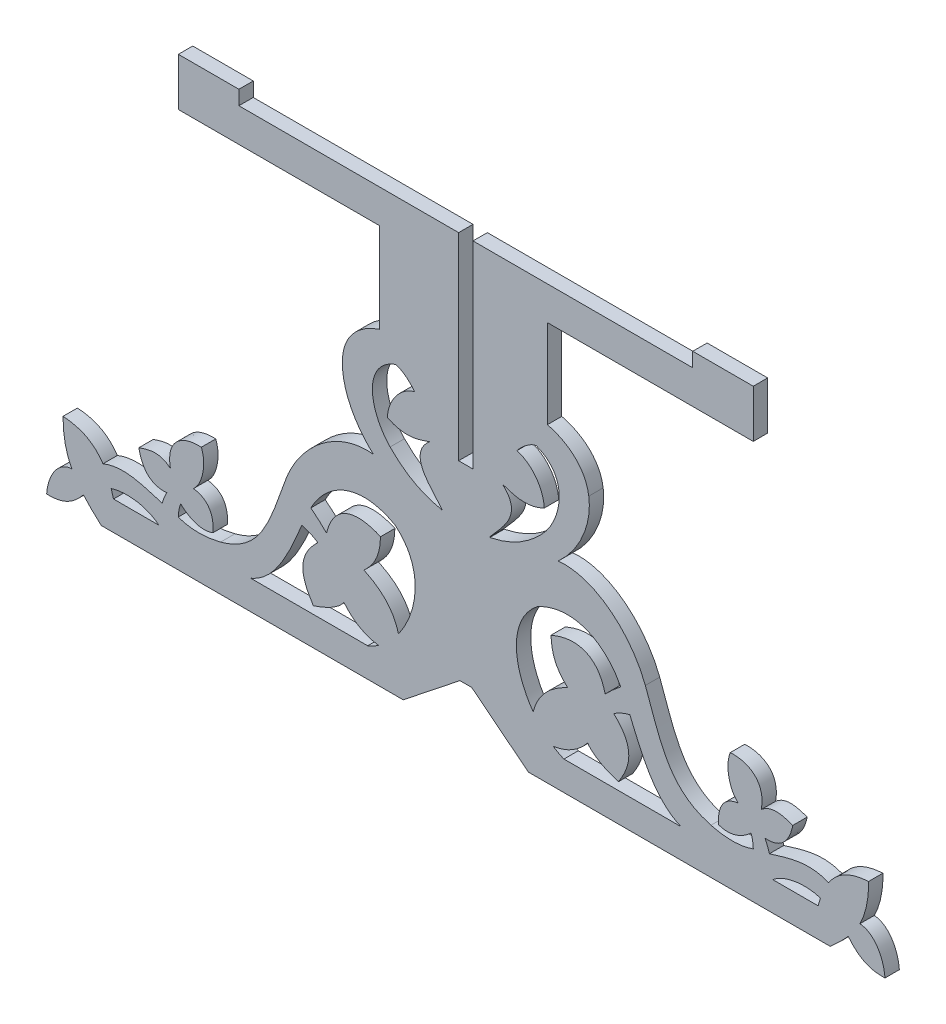
SolidWorks part; units mm, degrees
ref_plane "Plano frontal" through (0, 0, 0) normal (0, 0, 1) x (1, 0, 0)
ref_plane "Plano superior" through (0, 0, 0) normal (0, 1, 0) x (1, 0, 0)
ref_plane "Plano direito" through (0, 0, 0) normal (1, 0, 0) x (0, 0, -1)
sketch "Model" plane through (0, 0, 0) normal (0, 0, 1) x (1, 0, 0)
  line L0 (-10.7231, -37.6762) -> (-10.7231, -25.1897)
  line L1 (-10.7231, -25.1897) -> (-38.7386, -25.1897)
  line L2 (-38.7386, -18.5338) -> (-30.3175, -18.5338)
  line L3 (-30.3175, -18.5338) -> (-30.3175, -20.523)
  line L4 (-30.3175, -20.523) -> (0.2614, -20.523)
  line L5 (0.2614, -20.523) -> (0.2614, -48.0172)
  line L6 (0.2614, -48.0172) -> (2.2614, -48.0172)
  line L7 (2.2614, -48.0172) -> (2.2614, -20.523)
  line L8 (2.2614, -20.523) -> (32.8404, -20.523)
  line L9 (32.8404, -20.523) -> (32.8404, -18.5338)
  line L10 (32.8404, -18.5338) -> (41.2614, -18.5338)
  line L11 (41.2614, -25.1897) -> (12.6103, -25.1897)
  line L12 (12.6103, -25.1897) -> (12.6103, -37.4982)
  line L13 (51.9814, -80.6856) -> (9.9729, -80.6856)
  line L14 (9.9729, -80.6856) -> (2.0788, -74.4249)
  line L15 (2.0788, -74.4249) -> (0.4441, -74.4249)
  line L16 (0.4441, -74.4249) -> (-7.45, -80.6856)
  line L17 (-7.45, -80.6856) -> (-49.4585, -80.6856)
  line L18 (4.593, -55.0228) -> (4.593, -55.1006)
  line L19 (11.0703, -40.8025) -> (10.995, -40.8025)
  line L20 (-2.0702, -55.1006) -> (-2.0702, -55.0229)
  line L21 (-8.4723, -40.8025) -> (-8.5475, -40.8025)
  line L22 (31.2032, -76.6403) -> (14.9136, -76.6403)
  line L23 (50.289, -76.6403) -> (43.9782, -76.6403)
  line L24 (-28.6803, -76.6403) -> (-12.3907, -76.6403)
  line L25 (-47.7662, -76.6403) -> (-41.4553, -76.6403)
  spline S0 degree 3 poles (-49.4585, -80.6856) (-50.3937, -79.8491) (-51.2347, -79.0574) (-51.9577, -78.2277) knots 0 0 0 0 0.016393 0.016393 0.016393 0.016393
  spline S1 degree 3 poles (-51.9577, -78.2277) (-51.9788, -78.2553) (-52.0002, -78.2819) (-52.021, -78.3099) knots 0.016393 0.016393 0.016393 0.016393 0.032787 0.032787 0.032787 0.032787
  spline S2 degree 3 poles (-52.021, -78.3099) (-53.6044, -80.2428) (-55.1819, -80.7554) (-57.0719, -80.6857) knots 0.032787 0.032787 0.032787 0.032787 0.04918 0.04918 0.04918 0.04918
  spline S3 degree 3 poles (-57.0719, -80.6857) (-56.8686, -78.0981) (-55.414, -75.9909) (-53.5728, -75.8997) knots 0.04918 0.04918 0.04918 0.04918 0.065574 0.065574 0.065574 0.065574
  spline S4 degree 3 poles (-53.5728, -75.8997) (-54.3597, -74.3809) (-54.7976, -72.5861) (-54.7895, -70.1879) knots 0.065574 0.065574 0.065574 0.065574 0.081967 0.081967 0.081967 0.081967
  spline S5 degree 3 poles (-54.7895, -70.1879) (-52.2741, -70.3509) (-50.4738, -71.2581) (-49.2284, -73.1269) knots 0.081967 0.081967 0.081967 0.081967 0.098361 0.098361 0.098361 0.098361
  spline S6 degree 3 poles (-49.2284, -73.1269) (-46.411, -71.9547) (-43.74, -72.9249) (-40.9862, -73.7542) knots 0.098361 0.098361 0.098361 0.098361 0.114754 0.114754 0.114754 0.114754
  spline S7 degree 3 poles (-40.9862, -73.7542) (-40.8398, -73.2163) (-40.686, -72.8324) (-40.3544, -72.1812) knots 0.114754 0.114754 0.114754 0.114754 0.131148 0.131148 0.131148 0.131148
  spline S8 degree 3 poles (-40.3544, -72.1812) (-42.739, -72.3576) (-43.8155, -70.7839) (-44.2438, -68.7027) knots 0.131148 0.131148 0.131148 0.131148 0.147541 0.147541 0.147541 0.147541
  spline S9 degree 3 poles (-44.2438, -68.7027) (-42.5066, -68.0604) (-41.153, -67.8762) (-39.8456, -69.0009) knots 0.147541 0.147541 0.147541 0.147541 0.163934 0.163934 0.163934 0.163934
  spline S10 degree 3 poles (-39.8456, -69.0009) (-40.4823, -65.6416) (-38.2247, -64.1295) (-35.5393, -64.285) knots 0.163934 0.163934 0.163934 0.163934 0.180328 0.180328 0.180328 0.180328
  spline S11 degree 3 poles (-35.5393, -64.285) (-34.7662, -66.2296) (-35.4768, -68.8716) (-36.6561, -69.821) knots 0.180328 0.180328 0.180328 0.180328 0.196721 0.196721 0.196721 0.196721
  spline S12 degree 3 poles (-36.6561, -69.821) (-34.1328, -70.1006) (-33.7484, -72.4111) (-33.9344, -73.7949) knots 0.196721 0.196721 0.196721 0.196721 0.213115 0.213115 0.213115 0.213115
  spline S13 degree 3 poles (-33.9344, -73.7949) (-35.4592, -74.3589) (-37.082, -73.7999) (-38.4177, -72.5501) knots 0.213115 0.213115 0.213115 0.213115 0.229508 0.229508 0.229508 0.229508
  spline S14 degree 3 poles (-38.4177, -72.5501) (-38.5924, -72.9489) (-38.7578, -73.728) (-38.7393, -74.294) knots 0.229508 0.229508 0.229508 0.229508 0.245902 0.245902 0.245902 0.245902
  spline S15 degree 3 poles (-38.7393, -74.294) (-36.9185, -74.984) (-34.8066, -74.898) (-32.8571, -74.3775) knots 0.245902 0.245902 0.245902 0.245902 0.262295 0.262295 0.262295 0.262295
  spline S16 degree 3 poles (-32.8571, -74.3775) (-26.8946, -72.7859) (-25.8557, -67.7721) (-23.7202, -62.1023) knots 0.262295 0.262295 0.262295 0.262295 0.278689 0.278689 0.278689 0.278689
  spline S17 degree 3 poles (-23.7202, -62.1023) (-21.8469, -57.1289) (-16.8074, -52.6163) (-11.5988, -53.1702) knots 0.278689 0.278689 0.278689 0.278689 0.295082 0.295082 0.295082 0.295082
  spline S18 degree 3 poles (-11.5988, -53.1702) (-14.8451, -50.2251) (-16.2784, -46.3127) (-15.8499, -43.2265) knots 0.295082 0.295082 0.295082 0.295082 0.311475 0.311475 0.311475 0.311475
  spline S19 degree 3 poles (-15.8499, -43.2265) (-15.4451, -40.3111) (-13.2139, -38.4676) (-10.7231, -37.6762) knots 0.311475 0.311475 0.311475 0.311475 0.327869 0.327869 0.327869 0.327869
  spline S20 degree 3 poles (-38.7386, -25.1897) (-38.7386, -22.9711) (-38.7386, -20.7524) (-38.7386, -18.5338) knots 0.360656 0.360656 0.360656 0.360656 0.377049 0.377049 0.377049 0.377049
  spline S21 degree 3 poles (41.2614, -18.5338) (41.2614, -20.7524) (41.2614, -22.9711) (41.2614, -25.1897) knots 0.52459 0.52459 0.52459 0.52459 0.540984 0.540984 0.540984 0.540984
  spline S22 degree 3 poles (12.6103, -37.4982) (15.3469, -38.1638) (17.9338, -40.0649) (18.3727, -43.2265) knots 0.57377 0.57377 0.57377 0.57377 0.590164 0.590164 0.590164 0.590164
  spline S23 degree 3 poles (18.3727, -43.2265) (18.8013, -46.3127) (17.3679, -50.2251) (14.1216, -53.1702) knots 0.590164 0.590164 0.590164 0.590164 0.606557 0.606557 0.606557 0.606557
  spline S24 degree 3 poles (14.1216, -53.1702) (19.3303, -52.6163) (24.3698, -57.1289) (26.2431, -62.1023) knots 0.606557 0.606557 0.606557 0.606557 0.622951 0.622951 0.622951 0.622951
  spline S25 degree 3 poles (26.2431, -62.1023) (28.3786, -67.7721) (29.4175, -72.7859) (35.3799, -74.3775) knots 0.622951 0.622951 0.622951 0.622951 0.639344 0.639344 0.639344 0.639344
  spline S26 degree 3 poles (35.3799, -74.3775) (37.3294, -74.898) (39.4414, -74.984) (41.2622, -74.294) knots 0.639344 0.639344 0.639344 0.639344 0.655738 0.655738 0.655738 0.655738
  spline S27 degree 3 poles (41.2622, -74.294) (41.2806, -73.728) (41.1153, -72.9489) (40.9405, -72.5501) knots 0.655738 0.655738 0.655738 0.655738 0.672131 0.672131 0.672131 0.672131
  spline S28 degree 3 poles (40.9405, -72.5501) (39.6049, -73.7999) (37.9821, -74.3589) (36.4572, -73.7949) knots 0.672131 0.672131 0.672131 0.672131 0.688525 0.688525 0.688525 0.688525
  spline S29 degree 3 poles (36.4572, -73.7949) (36.2713, -72.4111) (36.6557, -70.1006) (39.179, -69.821) knots 0.688525 0.688525 0.688525 0.688525 0.704918 0.704918 0.704918 0.704918
  spline S30 degree 3 poles (39.179, -69.821) (37.9997, -68.8716) (37.2891, -66.2296) (38.0621, -64.285) knots 0.704918 0.704918 0.704918 0.704918 0.721311 0.721311 0.721311 0.721311
  spline S31 degree 3 poles (38.0621, -64.285) (40.7476, -64.1295) (43.0052, -65.6416) (42.3684, -69.0009) knots 0.721311 0.721311 0.721311 0.721311 0.737705 0.737705 0.737705 0.737705
  spline S32 degree 3 poles (42.3684, -69.0009) (43.6758, -67.8762) (45.0295, -68.0604) (46.7666, -68.7027) knots 0.737705 0.737705 0.737705 0.737705 0.754098 0.754098 0.754098 0.754098
  spline S33 degree 3 poles (46.7666, -68.7027) (46.3384, -70.7839) (45.2619, -72.3576) (42.8773, -72.1812) knots 0.754098 0.754098 0.754098 0.754098 0.770492 0.770492 0.770492 0.770492
  spline S34 degree 3 poles (42.8773, -72.1812) (43.2089, -72.8324) (43.3627, -73.2163) (43.5091, -73.7542) knots 0.770492 0.770492 0.770492 0.770492 0.786885 0.786885 0.786885 0.786885
  spline S35 degree 3 poles (43.5091, -73.7542) (46.2628, -72.9249) (48.9338, -71.9547) (51.7513, -73.1269) knots 0.786885 0.786885 0.786885 0.786885 0.803279 0.803279 0.803279 0.803279
  spline S36 degree 3 poles (51.7513, -73.1269) (52.9966, -71.2581) (54.7969, -70.3509) (57.3123, -70.1879) knots 0.803279 0.803279 0.803279 0.803279 0.819672 0.819672 0.819672 0.819672
  spline S37 degree 3 poles (57.3123, -70.1879) (57.3204, -72.5861) (56.8825, -74.3809) (56.0957, -75.8997) knots 0.819672 0.819672 0.819672 0.819672 0.836066 0.836066 0.836066 0.836066
  spline S38 degree 3 poles (56.0957, -75.8997) (57.9369, -75.9909) (59.3915, -78.0981) (59.5947, -80.6857) knots 0.836066 0.836066 0.836066 0.836066 0.852459 0.852459 0.852459 0.852459
  spline S39 degree 3 poles (59.5947, -80.6857) (57.7047, -80.7554) (56.1272, -80.2428) (54.5438, -78.3099) knots 0.852459 0.852459 0.852459 0.852459 0.868852 0.868852 0.868852 0.868852
  spline S40 degree 3 poles (54.5438, -78.3099) (54.5231, -78.2819) (54.5016, -78.2553) (54.4806, -78.2277) knots 0.868852 0.868852 0.868852 0.868852 0.885246 0.885246 0.885246 0.885246
  spline S41 degree 3 poles (54.4806, -78.2277) (53.7575, -79.0574) (52.9166, -79.8491) (51.9814, -80.6856) knots 0.885246 0.885246 0.885246 0.885246 0.901639 0.901639 0.901639 0.901639
  spline S42 degree 3 poles (4.593, -55.1006) (7.4607, -54.4947) (9.6337, -53.3337) (11.7968, -51.1256) knots 0.111111 0.111111 0.111111 0.111111 0.222222 0.222222 0.222222 0.222222
  spline S43 degree 3 poles (11.7968, -51.1256) (14.6104, -48.2536) (15.7932, -42.5892) (11.0703, -40.8025) knots 0.222222 0.222222 0.222222 0.222222 0.333333 0.333333 0.333333 0.333333
  spline S44 degree 3 poles (10.995, -40.8025) (10.0422, -40.9908) (8.9013, -42.0568) (8.3751, -42.7392) knots 0.444444 0.444444 0.444444 0.444444 0.555556 0.555556 0.555556 0.555556
  spline S45 degree 3 poles (8.3751, -42.7392) (10.5216, -43.3581) (12.0847, -45.5727) (12.1767, -47.7616) knots 0.555556 0.555556 0.555556 0.555556 0.666667 0.666667 0.666667 0.666667
  spline S46 degree 3 poles (12.1767, -47.7616) (9.9511, -48.8776) (8.1387, -48.4392) (6.3426, -47.765) knots 0.666667 0.666667 0.666667 0.666667 0.777778 0.777778 0.777778 0.777778
  spline S47 degree 3 poles (6.3426, -47.765) (9.272, -50.3777) (6.4959, -52.7581) (4.593, -55.0228) knots 0.777778 0.777778 0.777778 0.777778 1 1 1 1
  spline S48 degree 3 poles (-2.0702, -55.0229) (-3.973, -52.7582) (-6.7492, -50.3777) (-3.8197, -47.765) knots 0.111111 0.111111 0.111111 0.111111 0.222222 0.222222 0.222222 0.222222
  spline S49 degree 3 poles (-3.8197, -47.765) (-5.6159, -48.4392) (-7.4282, -48.8776) (-9.6538, -47.7616) knots 0.222222 0.222222 0.222222 0.222222 0.333333 0.333333 0.333333 0.333333
  spline S50 degree 3 poles (-9.6538, -47.7616) (-9.5618, -45.5727) (-7.9987, -43.3581) (-5.8522, -42.7392) knots 0.333333 0.333333 0.333333 0.333333 0.444444 0.444444 0.444444 0.444444
  spline S51 degree 3 poles (-5.8522, -42.7392) (-6.3784, -42.0568) (-7.5194, -40.9908) (-8.4723, -40.8025) knots 0.444444 0.444444 0.444444 0.444444 0.555556 0.555556 0.555556 0.555556
  spline S52 degree 3 poles (-8.5475, -40.8025) (-13.2704, -42.5892) (-12.0875, -48.2536) (-9.274, -51.1256) knots 0.666667 0.666667 0.666667 0.666667 0.777778 0.777778 0.777778 0.777778
  spline S53 degree 3 poles (-9.274, -51.1256) (-7.1108, -53.3337) (-4.9378, -54.4947) (-2.0702, -55.1006) knots 0.777778 0.777778 0.777778 0.777778 1 1 1 1
  spline S54 degree 3 poles (11.1779, -60.1432) (15.7255, -57.6243) (20.4073, -59.3728) (22.8252, -63.985) knots 0 0 0 0 0.142857 0.142857 0.142857 0.142857
  spline S55 degree 3 poles (22.8252, -63.985) (22.0172, -64.6261) (21.246, -65.3009) (20.6496, -65.9328) knots 0.142857 0.142857 0.142857 0.142857 0.285714 0.285714 0.285714 0.285714
  spline S56 degree 3 poles (20.6496, -65.9328) (19.5974, -61.6749) (16.4549, -61.1629) (13.1258, -62.6016) knots 0.285714 0.285714 0.285714 0.285714 0.428571 0.428571 0.428571 0.428571
  spline S57 degree 3 poles (13.1258, -62.6016) (13.1923, -64.5173) (13.6493, -66.1778) (15.4372, -67.7712) knots 0.428571 0.428571 0.428571 0.428571 0.571429 0.571429 0.571429 0.571429
  spline S58 degree 3 poles (15.4372, -67.7712) (13.0142, -68.9095) (11.2762, -70.5694) (10.6359, -73.0882) knots 0.571429 0.571429 0.571429 0.571429 0.714286 0.714286 0.714286 0.714286
  spline S59 degree 3 poles (10.6359, -73.0882) (7.8828, -69.2377) (6.9885, -63.4865) (11.1779, -60.1432) knots 0.714286 0.714286 0.714286 0.714286 1 1 1 1
  spline S60 degree 3 poles (13.4069, -75.8435) (15.2432, -75.5811) (16.8695, -74.7264) (18.2249, -73.0522) knots 0 0 0 0 0.125 0.125 0.125 0.125
  spline S61 degree 3 poles (18.2249, -73.0522) (19.0084, -74.2501) (21.0144, -75.1409) (22.4861, -75.594) knots 0.125 0.125 0.125 0.125 0.25 0.25 0.25 0.25
  spline S62 degree 3 poles (22.4861, -75.594) (24.1211, -73.1005) (24.9424, -70.5429) (21.8417, -67.6767) knots 0.25 0.25 0.25 0.25 0.375 0.375 0.375 0.375
  spline S63 degree 3 poles (21.8417, -67.6767) (22.5603, -67.2185) (23.3218, -66.8869) (24.0798, -66.6989) knots 0.375 0.375 0.375 0.375 0.5 0.5 0.5 0.5
  spline S64 degree 3 poles (24.0798, -66.6989) (25.6529, -70.3508) (27.4424, -75.0949) (31.2032, -76.6403) knots 0.5 0.5 0.5 0.5 0.625 0.625 0.625 0.625
  spline S65 degree 3 poles (14.9136, -76.6403) (14.3993, -76.4413) (13.8945, -76.1717) (13.4069, -75.8435) knots 0.75 0.75 0.75 0.75 1 1 1 1
  spline S66 degree 3 poles (50.6137, -75.5322) (50.4966, -75.8825) (50.3884, -76.2514) (50.289, -76.6403) knots 0 0 0 0 0.25 0.25 0.25 0.25
  spline S67 degree 3 poles (43.9782, -76.6403) (45.4021, -75.4281) (48.0767, -74.7811) (50.6137, -75.5322) knots 0.5 0.5 0.5 0.5 1 1 1 1
  spline S68 degree 3 poles (-8.6551, -60.1432) (-13.2026, -57.6243) (-17.8845, -59.3728) (-20.3024, -63.985) knots 0 0 0 0 0.142857 0.142857 0.142857 0.142857
  spline S69 degree 3 poles (-20.3024, -63.985) (-19.4943, -64.6261) (-18.7232, -65.3009) (-18.1268, -65.9328) knots 0.142857 0.142857 0.142857 0.142857 0.285714 0.285714 0.285714 0.285714
  spline S70 degree 3 poles (-18.1268, -65.9328) (-17.0746, -61.6749) (-13.932, -61.1629) (-10.6029, -62.6016) knots 0.285714 0.285714 0.285714 0.285714 0.428571 0.428571 0.428571 0.428571
  spline S71 degree 3 poles (-10.6029, -62.6016) (-10.6694, -64.5173) (-11.1264, -66.1778) (-12.9143, -67.7712) knots 0.428571 0.428571 0.428571 0.428571 0.571429 0.571429 0.571429 0.571429
  spline S72 degree 3 poles (-12.9143, -67.7712) (-10.4913, -68.9095) (-8.7533, -70.5694) (-8.113, -73.0882) knots 0.571429 0.571429 0.571429 0.571429 0.714286 0.714286 0.714286 0.714286
  spline S73 degree 3 poles (-8.113, -73.0882) (-5.3599, -69.2377) (-4.4657, -63.4865) (-8.6551, -60.1432) knots 0.714286 0.714286 0.714286 0.714286 1 1 1 1
  spline S74 degree 3 poles (-10.884, -75.8435) (-12.7203, -75.5811) (-14.3466, -74.7264) (-15.7021, -73.0522) knots 0 0 0 0 0.125 0.125 0.125 0.125
  spline S75 degree 3 poles (-15.7021, -73.0522) (-16.4855, -74.2501) (-18.4916, -75.1409) (-19.9632, -75.594) knots 0.125 0.125 0.125 0.125 0.25 0.25 0.25 0.25
  spline S76 degree 3 poles (-19.9632, -75.594) (-21.5983, -73.1005) (-22.4196, -70.5429) (-19.3188, -67.6767) knots 0.25 0.25 0.25 0.25 0.375 0.375 0.375 0.375
  spline S77 degree 3 poles (-19.3188, -67.6767) (-20.0374, -67.2185) (-20.7989, -66.8869) (-21.557, -66.6989) knots 0.375 0.375 0.375 0.375 0.5 0.5 0.5 0.5
  spline S78 degree 3 poles (-21.557, -66.6989) (-23.1301, -70.3508) (-24.9195, -75.0949) (-28.6803, -76.6403) knots 0.5 0.5 0.5 0.5 0.625 0.625 0.625 0.625
  spline S79 degree 3 poles (-12.3907, -76.6403) (-11.8765, -76.4413) (-11.3717, -76.1717) (-10.884, -75.8435) knots 0.75 0.75 0.75 0.75 1 1 1 1
  spline S80 degree 3 poles (-48.0908, -75.5322) (-47.9737, -75.8825) (-47.8655, -76.2514) (-47.7662, -76.6403) knots 0 0 0 0 0.25 0.25 0.25 0.25
  spline S81 degree 3 poles (-41.4553, -76.6403) (-42.8792, -75.4281) (-45.5538, -74.7811) (-48.0908, -75.5322) knots 0.5 0.5 0.5 0.5 1 1 1 1
extrude "Ressalto-extrusão1" add sketch "Model" along normal blind 2
